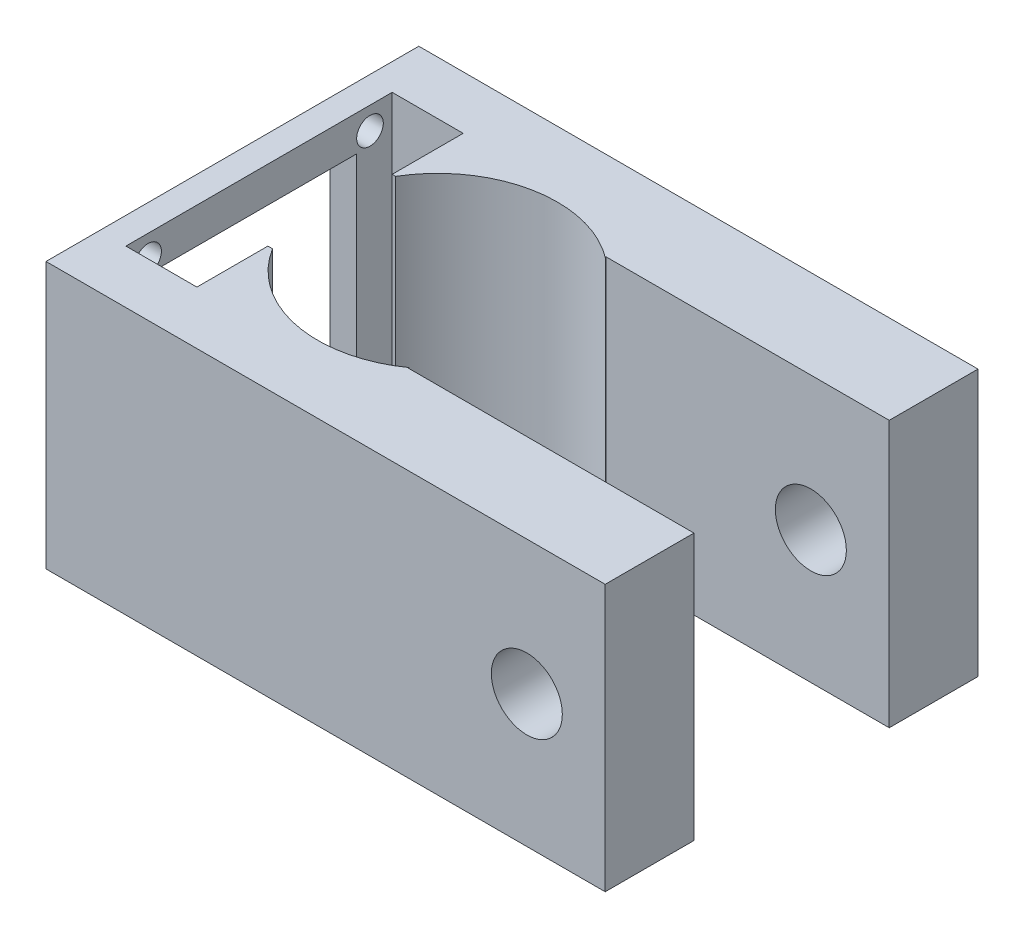
SolidWorks part; units mm, degrees
ref_plane "Alzado" through (0, 0, 0) normal (0, 0, 1) x (1, 0, 0)
ref_plane "Planta" through (0, 0, 0) normal (0, 1, 0) x (1, 0, 0)
ref_plane "Vista lateral" through (0, 0, 0) normal (1, 0, 0) x (0, 0, -1)
sketch "Croquis1" plane through (0, 0, 0) normal (1, 0, 0) x (0, 0, -1)
  line L0 (-0.1071, 15.1071) -> (-0.1071, -14.8929) construction
  line L1 (-15.1071, 15.1071) -> (14.8929, 15.1071)
  line L2 (-15.1071, 15.1071) -> (-15.1071, -14.8929)
  line L3 (-15.1071, -14.8929) -> (14.8929, -14.8929)
  line L4 (14.8929, 15.1071) -> (14.8929, -14.8929)
  line L5 (-11.1071, 11.1071) -> (10.8929, 11.1071)
  line L6 (-11.1071, 11.1071) -> (-11.1071, -10.8929)
  line L7 (-11.1071, -10.8929) -> (10.8929, -10.8929)
  line L8 (10.8929, 11.1071) -> (10.8929, -10.8929)
  line L9 (-15.1071, 0.1071) -> (14.8929, 0.1071) construction
  circle A0 centre (-12.6071, 12.6071) radius 1.5
  circle A1 centre (12.3929, 12.6071) radius 1.5
  circle A2 centre (12.3929, -12.3929) radius 1.5
  circle A3 centre (-12.6071, -12.3929) radius 1.5
  dimension "D7" = 3
  dimension "D1" = 30
  dimension "D2" = 30
  dimension "D3" = 4
  dimension "D4" = 4
  dimension "D5" = 4
  dimension "D6" = 4
  dimension "D8" = 2.5
  dimension "D9" = 2.5
extrude "Saliente-Extruir1" add sketch "Croquis1" along normal blind 3
sketch "Croquis2" plane through (0, 15.1071, 0) normal (0, 1, 0) x (1, 0, 0)
  line L1 (0, -15.1071) -> (2.9987, -15.1071)
  line L2 (0, -15.1071) -> (0, -21.1071)
  line L3 (0, -21.1071) -> (2.9987, -21.1071)
  line L4 (2.9987, -15.1071) -> (2.9987, -21.1071)
  line L5 (0, 14.8929) -> (2.9987, 14.8929)
  line L6 (0, 14.8929) -> (0, 20.8929)
  line L7 (0, 20.8929) -> (2.9987, 20.8929)
  line L8 (2.9987, 14.8929) -> (2.9987, 20.8929)
  dimension "D1" = 6
  dimension "D2" = 6
extrude "Saliente-Extruir2" add sketch "Croquis2" against normal blind 30
sketch "Croquis3" plane through (2.9987, 0, 0) normal (1, 0, 0) x (0, 0, -1)
  line L1 (-21.1071, 15.1071) -> (-15.1071, 15.1071)
  line L2 (-21.1071, 15.1071) -> (-21.1071, -14.8929)
  line L3 (-21.1071, -14.8929) -> (-15.1071, -14.8929)
  line L4 (-15.1071, 15.1071) -> (-15.1071, -14.8929)
  line L5 (14.8929, 15.1071) -> (20.8929, 15.1071)
  line L6 (14.8929, 15.1071) -> (14.8929, -14.8929)
  line L7 (14.8929, -14.8929) -> (20.8929, -14.8929)
  line L8 (20.8929, 15.1071) -> (20.8929, -14.8929)
extrude "Saliente-Extruir3" add sketch "Croquis3" along normal blind 40
sketch "Croquis5" plane through (0, 15.1071, 0) normal (0, 1, 0) x (1, 0, 0)
  line L5 (2.9993, 14.8929) -> (2.9993, -15.1071) construction
  line L6 (42.9987, -15.1071) -> (10.9993, -15.1071)
  line L7 (42.9987, -15.1071) -> (42.9987, -7.1071)
  line L8 (42.9987, -7.1071) -> (10.9993, -7.1071)
  line L9 (10.9993, -15.1071) -> (10.9993, -7.1071)
  line L10 (42.9987, 14.8929) -> (2.9993, 14.8929) construction
  line L11 (10.9993, 14.8929) -> (42.9987, 14.8929)
  line L12 (10.9993, 14.8929) -> (10.9993, 6.8929)
  line L13 (10.9993, 6.8929) -> (42.9987, 6.8929)
  line L14 (42.9987, 14.8929) -> (42.9987, 6.8929)
  dimension "D1" = 8
  dimension "D2" = 8
  dimension "D3" = 8
extrude "Saliente-Extruir5" add sketch "Croquis5" against normal blind 30
sketch "Croquis6" plane through (0, 15.1071, 0) normal (0, 1, 0) x (1, 0, 0)
  line L0 (2.9993, 14.8929) -> (2.9993, -15.1071) construction
  circle A0 centre (22.9993, 0) radius 13.5
  dimension "D1" = 27
  dimension "D2" = 20
extrude "Cortar-Extruir1" cut sketch "Croquis6" against normal blind 30
sketch "Croquis7" plane through (42.9987, 0, 0) normal (1, 0, 0) x (0, 0, -1)
  line L1 (-21.1071, 15.1071) -> (-7.1071, 15.1071)
  line L2 (-21.1071, 15.1071) -> (-21.1071, -14.8929)
  line L3 (-21.1071, -14.8929) -> (-7.1071, -14.8929)
  line L4 (-7.1071, 15.1071) -> (-7.1071, -14.8929)
  line L5 (6.8929, 15.1071) -> (20.8929, 15.1071)
  line L6 (6.8929, 15.1071) -> (6.8929, -14.8929)
  line L7 (6.8929, -14.8929) -> (20.8929, -14.8929)
  line L8 (20.8929, 15.1071) -> (20.8929, -14.8929)
extrude "Saliente-Extruir6" add sketch "Croquis7" along normal blind 20
sketch "Croquis8" plane through (0, 15.1071, 0) normal (0, 1, 0) x (1, 0, 0)
  line L0 (62.9987, 6.8929) -> (62.9987, 10.8929)
  line L1 (62.9987, 20.8929) -> (62.9987, 6.8929) construction
  line L2 (62.9987, 10.8929) -> (31.1091, 10.8929)
  line L5 (62.9987, -7.1071) -> (62.9987, -11.1071)
  line L6 (62.9987, -7.1071) -> (62.9987, -21.1071) construction
  line L7 (62.9987, -11.1071) -> (30.8131, -11.1071)
  line L10 (31.1091, 10.8929) -> (31.1091, 6.8929)
  line L11 (31.1091, 6.8929) -> (62.9987, 6.8929)
  line L14 (30.8131, -11.1071) -> (30.8131, -7.1071)
  line L15 (30.8131, -7.1071) -> (62.9987, -7.1071)
  dimension "D1" = 4
  dimension "D2" = 4
extrude "Cortar-Extruir2" cut sketch "Croquis8" against normal blind 46
sketch "Croquis9" plane through (0, 0, -10.8929) normal (0, 0, 1) x (1, 0, 0)
  circle A0 centre (54.1681, 0) radius 4
  dimension "D1" = 8
extrude "Cortar-Extruir3" cut sketch "Croquis9" along normal blind 70 and the other way blind 48
